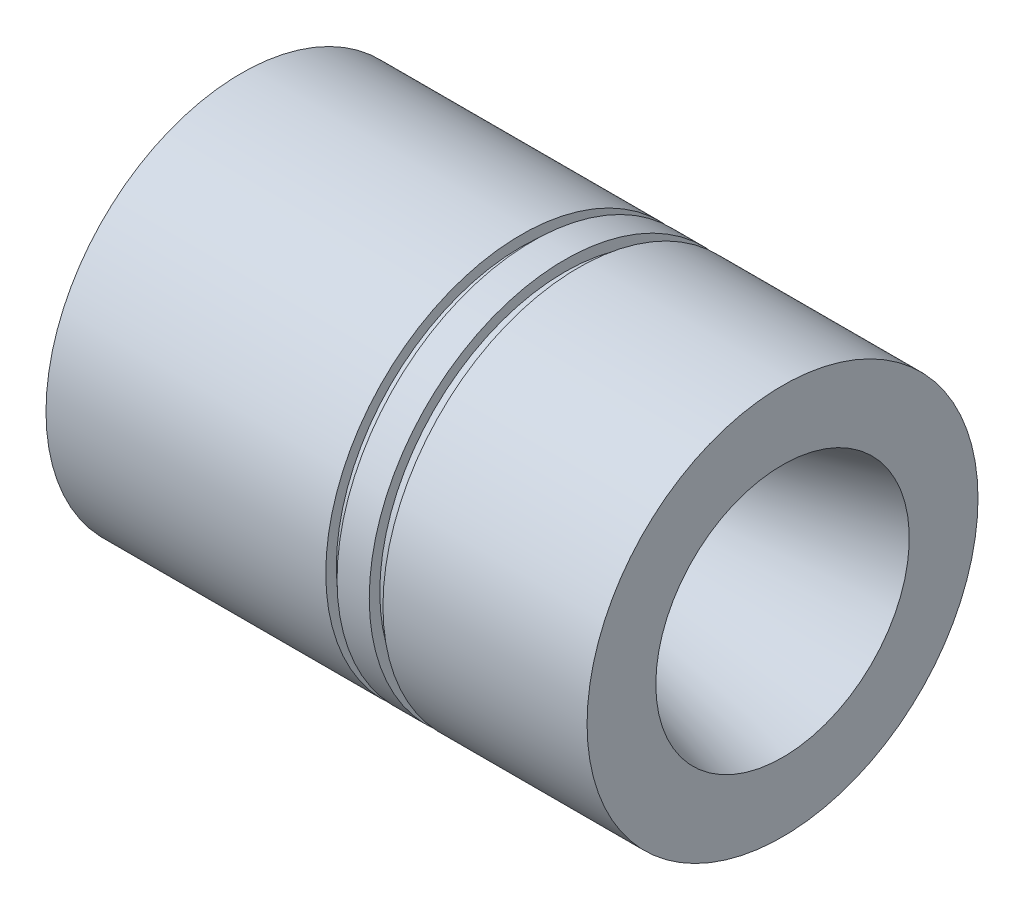
SolidWorks part; units mm, degrees
ref_plane "Front Plane" through (0, 0, 0) normal (0, 0, 1) x (1, 0, 0)
ref_plane "Top Plane" through (0, 0, 0) normal (0, 1, 0) x (1, 0, 0)
ref_plane "Right Plane" through (0, 0, 0) normal (1, 0, 0) x (0, 0, -1)
sketch "Sketch1" plane through (0, 0, 0) normal (0, 0, 1) x (1, 0, 0)
  line L0 (0, 0) -> (176.8872, 0) construction
  line L1 (0, 41.402) -> (27.5254, 41.402) construction
  line L2 (54.4274, 15.367) -> (96.5346, 15.367) construction
  line L3 (43.421, 29.9014) -> (63.3028, 18.4227)
  line L5 (75.8244, 15.5643) -> (140.97, 33.02)
  line L7 (0, 41.402) -> (0, 50.927)
  line L8 (0, 50.927) -> (72.8929, 50.927)
  line L9 (140.97, 50.927) -> (140.97, 33.02)
  line L10 (72.8929, 50.927) -> (72.8929, 48.1802)
  line L11 (72.8929, 48.1802) -> (75.8244, 48.1802)
  line L12 (75.8244, 48.1802) -> (75.8244, 50.927)
  line L13 (84.2185, 50.927) -> (84.2185, 48.1802)
  line L14 (84.2185, 48.1802) -> (87.7885, 48.1802)
  line L15 (87.7885, 48.1802) -> (87.7885, 50.927)
  line L16 (75.8244, 50.927) -> (84.2185, 50.927)
  line L17 (87.7885, 50.927) -> (140.97, 50.927)
  arc A0 (0, 41.402) -> (43.421, 29.9014) centre (0.495, -44.4486) cw
  arc A1 (74.168, 15.367) -> (63.3028, 18.4227) centre (74.7328, 38.22) cw
  arc A2 (74.168, 15.367) -> (75.8244, 15.5643) centre (74.3123, 21.2072) ccw
  dimension "D4" = 22.86
  dimension "D5" = 74.168
  dimension "D7" = 5.842
  dimension "D11" = 9.525
  dimension "D6" = 30
  dimension "D3" = 85.852
  dimension "D9" = 66.802
  dimension "D1" = 41.402
  dimension "D2" = 15.367
  dimension "D8" = 15
  dimension "D10" = 33.02
revolve "Revolve1" add sketch "Sketch1" angle 360 about L0
